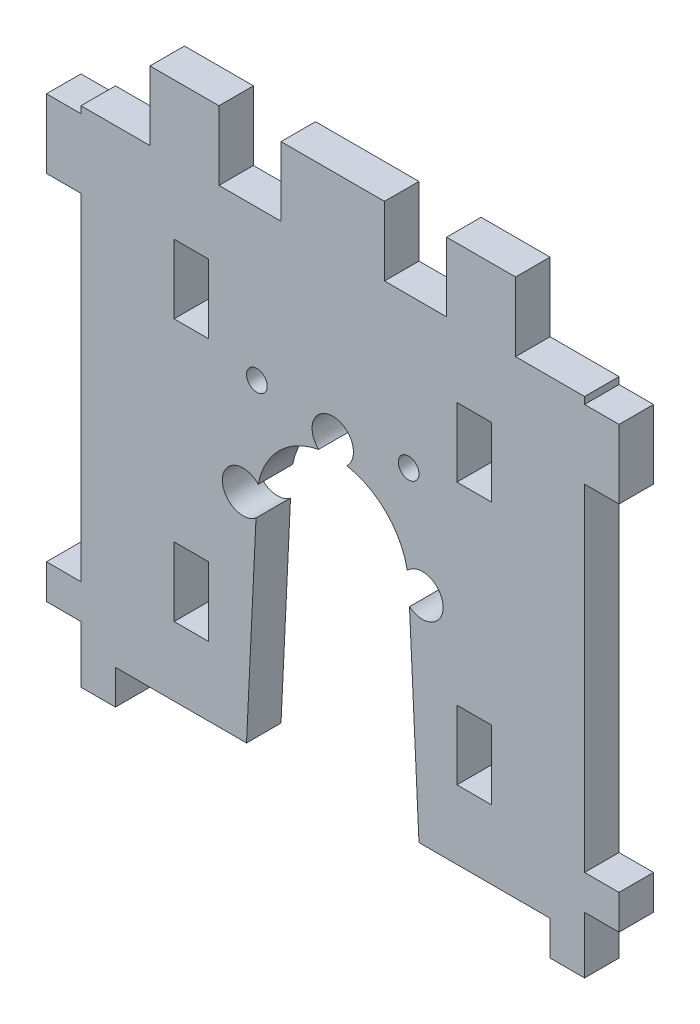
SolidWorks part; units mm, degrees
ref_plane "Plan de face" through (0, 0, 0) normal (0, 0, 1) x (1, 0, 0)
ref_plane "Plan de dessus" through (0, 0, 0) normal (0, 1, 0) x (1, 0, 0)
ref_plane "Plan de droite" through (0, 0, 0) normal (1, 0, 0) x (0, 0, -1)
sketch "Esquisse1" plane through (0, 0, 0) normal (0, 0, 1) x (1, 0, 0)
  line L0 (0, 0) -> (29, 0)
  line L1 (29, 0) -> (30.5124, 31.7976)
  line L2 (0, 0) -> (0, 73)
  line L3 (0, 73) -> (83, 73)
  line L4 (83, 0) -> (54, 0)
  line L5 (54, 0) -> (52.4876, 31.7976)
  line L6 (83, 0) -> (83, 73)
  line L8 (41.5, 31.275) -> (41.5, 0) construction
  arc A0 (30.5124, 31.7976) -> (52.4876, 31.7976) centre (41.5, 31.275) cw
  dimension "D3" = 11
  dimension "D1" = 83
  dimension "D2" = 73
  dimension "D4" = 25
extrude "Boss.-Extru.1" add sketch "Esquisse1" along normal blind 5
sketch "Esquisse3" plane through (0, 0, 5) normal (0, 0, 1) x (1, 0, 0)
  line L0 (83, 73) -> (0, 73) construction
  line L1 (15, 73) -> (0, 73)
  line L2 (15, 73) -> (15, 68)
  line L3 (15, 68) -> (5, 68)
  line L4 (0, 73) -> (0, 67)
  line L5 (0, 73) -> (0, 0) construction
  line L6 (78, 67) -> (83, 67)
  line L7 (5, 8.25) -> (0, 8.25) construction
  line L8 (5, 57) -> (0, 57)
  line L9 (5, 57) -> (5, 8.25)
  line L10 (5, 8.25) -> (0, 8.25)
  line L11 (0, 57) -> (0, 8.25)
  line L12 (41.5, 31.275) -> (41.5, 0) construction
  line L13 (5, 3.25) -> (0, 3.25)
  line L14 (5, 3.25) -> (5, 0)
  line L15 (5, 0) -> (0, 0)
  line L16 (0, 3.25) -> (0, 0)
  line L17 (83, 3.25) -> (83, 0)
  line L18 (78, 0) -> (83, 0)
  line L19 (78, 3.25) -> (78, 0)
  line L20 (78, 3.25) -> (83, 3.25)
  line L21 (83, 57) -> (83, 8.25)
  line L22 (78, 8.25) -> (83, 8.25)
  line L23 (78, 57) -> (78, 8.25)
  line L24 (78, 57) -> (83, 57)
  line L25 (83, 73) -> (83, 67)
  line L26 (83, 73) -> (0, 73) construction
  line L27 (68, 73) -> (68, 68)
  line L28 (68, 73) -> (83, 73)
  line L29 (64.5, 20) -> (64.5, 10)
  line L30 (23.5, 58) -> (18.5, 58)
  line L31 (23.5, 58) -> (23.5, 48)
  line L32 (23.5, 48) -> (18.5, 48)
  line L33 (18.5, 58) -> (18.5, 48)
  line L34 (23.5, 20) -> (18.5, 20)
  line L35 (23.5, 20) -> (23.5, 10)
  line L36 (23.5, 10) -> (18.5, 10)
  line L37 (18.5, 20) -> (18.5, 10)
  line L38 (59.5, 10) -> (64.5, 10)
  line L39 (59.5, 20) -> (59.5, 10)
  line L40 (59.5, 20) -> (64.5, 20)
  line L41 (64.5, 58) -> (64.5, 48)
  line L42 (59.5, 48) -> (64.5, 48)
  line L43 (59.5, 58) -> (59.5, 48)
  line L44 (59.5, 58) -> (64.5, 58)
  line L45 (5, 68) -> (5, 67)
  line L46 (5, 67) -> (0, 67)
  line L47 (78, 68) -> (78, 67)
  line L48 (68, 68) -> (78, 68)
  line L49 (58, 73) -> (49, 73)
  line L50 (58, 73) -> (58, 68)
  line L51 (58, 68) -> (49, 68)
  line L52 (49, 73) -> (49, 68)
  line L53 (58, 68) -> (58, 73) construction
  line L54 (25, 68) -> (25, 73) construction
  line L55 (25, 73) -> (34, 73)
  line L56 (25, 73) -> (25, 68)
  line L57 (25, 68) -> (34, 68)
  line L58 (34, 73) -> (34, 68)
  circle A0 centre (41.5, 44.275) radius 3
  circle A1 centre (54.5, 31.275) radius 3
  circle A2 centre (28.5, 31.275) radius 3
  dimension "D2" = 6
  dimension "D3" = 6
  dimension "D4" = 6
  dimension "D1" = 15
  dimension "D5" = 10
  dimension "D6" = 15
  dimension "D7" = 36
  dimension "D8" = 5
  dimension "D9" = 5
  dimension "D10" = 6
  dimension "D11" = 5
extrude "Enlèv. mat.-Extru.1" cut sketch "Esquisse3" against normal blind 5
sketch "Esquisse4" plane through (0, 0, 0) normal (0, 0, -1) x (-1, 0, 0)
  line L0 (-34, 68) -> (-34, 73) construction
  line L1 (-68, 73) -> (-58, 73)
  line L2 (-68, 73) -> (-68, 78)
  line L3 (-68, 78) -> (-58, 78)
  line L4 (-58, 73) -> (-58, 78)
  line L5 (-49, 73) -> (-34, 73)
  line L6 (-49, 73) -> (-49, 78)
  line L7 (-49, 78) -> (-34, 78)
  line L8 (-34, 73) -> (-34, 78)
  line L9 (-25, 73) -> (-15, 73)
  line L10 (-25, 73) -> (-25, 78)
  line L11 (-25, 78) -> (-15, 78)
  line L12 (-15, 73) -> (-15, 78)
  line L13 (-49, 73) -> (-34, 73) construction
  line L14 (-41.5, 73) -> (-41.5, 0) construction
  line L15 (-78, 0) -> (-73, 0)
  line L16 (-78, 0) -> (-78, -5)
  line L17 (-78, -5) -> (-73, -5)
  line L18 (-73, 0) -> (-73, -5)
  line L19 (191.3876, 0) -> (-188.6124, 0) construction
  line L20 (-10, 0) -> (-10, -5)
  line L21 (-5, -5) -> (-10, -5)
  line L22 (-5, 0) -> (-5, -5)
  line L23 (-5, 0) -> (-10, 0)
  dimension "D1" = 5
extrude "Boss.-Extru.2" add sketch "Esquisse4" against normal blind 5
sketch "Esquisse5" plane through (0, 0, 5) normal (0, 0, 1) x (1, 0, 0)
  circle A0 centre (52.5, 46.275) radius 1.5
  circle A1 centre (30.5, 46.275) radius 1.5
extrude "Enlèv. mat.-Extru.2" cut sketch "Esquisse5" against normal blind 5
